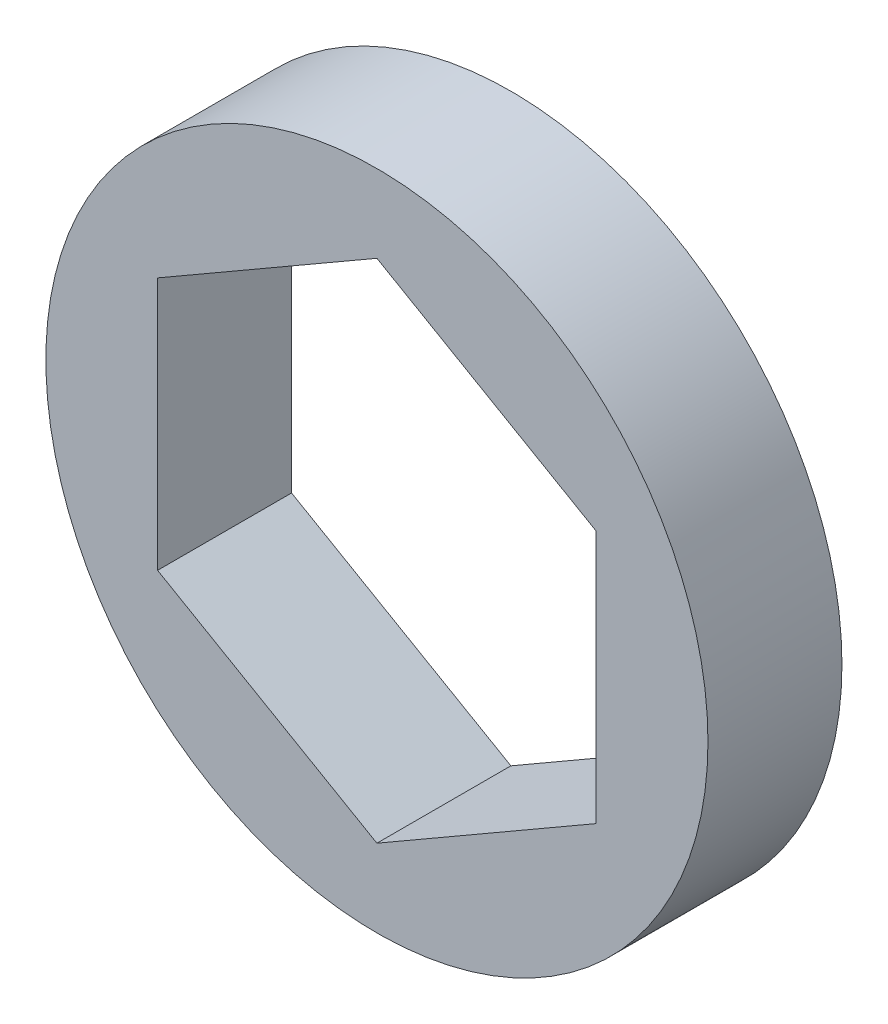
SolidWorks part; units mm, degrees
material "Nylon 101"
ref_plane "Front Plane" through (0, 0, 0) normal (0, 0, 1) x (1, 0, 0)
ref_plane "Top Plane" through (0, 0, 0) normal (0, 1, 0) x (1, 0, 0)
ref_plane "Right Plane" through (0, 0, 0) normal (1, 0, 0) x (0, 0, -1)
sketch "Sketch1" plane through (0, 0, 0) normal (0, 0, 1) x (1, 0, 0)
  line L1 (6.731, 3.8861) -> (0, 7.7723)
  line L2 (0, 7.7723) -> (-6.731, 3.8861)
  line L3 (-6.731, 3.8861) -> (-6.731, -3.8861)
  line L4 (-6.731, -3.8861) -> (0, -7.7723)
  line L5 (0, -7.7723) -> (6.731, -3.8861)
  line L6 (6.731, -3.8861) -> (6.731, 3.8861)
  circle A0 centre (0, 0) radius 6.731 construction
  circle A1 centre (0, 0) radius 10.16
  dimension "D1" = 13.462
  dimension "D2" = 20.32
extrude "Boss-Extrude1" add sketch "Sketch1" along normal blind 4.112
